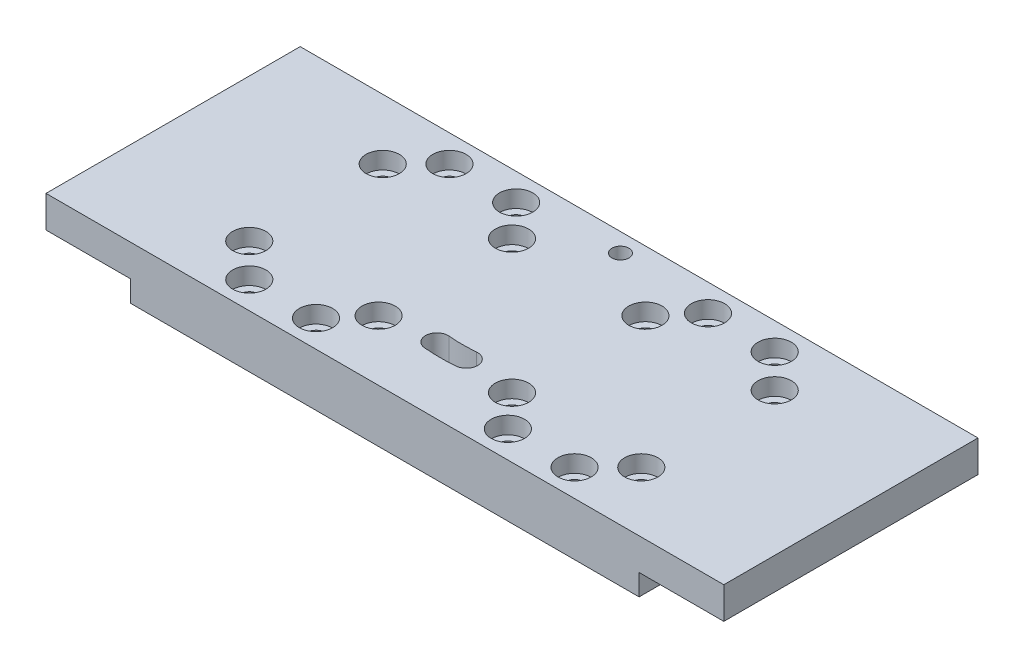
SolidWorks part; units mm, degrees
ref_plane "Front Plane" through (0, 0, 0) normal (0, 0, 1) x (1, 0, 0)
ref_plane "Top Plane" through (0, 0, 0) normal (0, 1, 0) x (1, 0, 0)
ref_plane "Right Plane" through (0, 0, 0) normal (1, 0, 0) x (0, 0, -1)
sketch "Sketch1" plane through (0, 0, 0) normal (0, 1, 0) x (1, 0, 0)
  line L1 (-101.6, -38.1) -> (101.6, -38.1)
  line L2 (-101.6, -38.1) -> (-101.6, 38.1)
  line L3 (-101.6, 38.1) -> (101.6, 38.1)
  line L4 (101.6, -38.1) -> (101.6, 38.1)
  line L5 (-101.6, -38.1) -> (101.6, 38.1) construction
  line L6 (-101.6, 38.1) -> (101.6, -38.1) construction
  point P0 (0, 0)
  dimension "D1" = 76.2
  dimension "D2" = 203.2
extrude "Boss-Extrude1" add sketch "Sketch1" along normal blind 15.875
hole_wizard "1/4-20 Tapped Hole1" positions "Sketch2" profile "Sketch3" tap size "1/4-20" standard "ANSI Inch" end condition through all
sketch "Sketch2" plane through (0, 15.875, 0) normal (0, 1, 0) x (1, 0, 0)
  point P0 (0, 32.5)
cosmetic thread "Hole Thread1" parameters "D2"=6.35
sketch "Sketch3" plane through (0, 15.875, -32.5) normal (1, 0, 0) x (0, 0, 1)
  line L0 (0, 0) -> (0, 15.875)
  line L1 (0, 15.875) -> (2.5527, 15.875)
  line L2 (2.5527, 15.875) -> (2.5527, 0)
  line L5 (2.5527, 0) -> (0, 0)
  line L11 (0, -6.35) -> (0, 107.95) construction
  dimension "Thru Tap Drill Dia." = 5.1054
  dimension "Thru Tap Drill Depth" = 15.875
sketch "Sketch4" plane through (0, 15.875, 0) normal (0, 1, 0) x (1, 0, 0)
  line L0 (0, -18.3) -> (0, 32.5) construction
  arc A0 (-4.4275, -18.1067) -> (4.4275, -18.1067) centre (0, 32.5) ccw construction
  arc A1 (-4.7215, -21.4673) -> (4.7215, -21.4673) centre (0, 32.5) ccw
  arc A2 (-4.1335, -14.7461) -> (4.1335, -14.7461) centre (0, 32.5) ccw
  arc A3 (-4.1335, -14.7461) -> (-4.7215, -21.4673) centre (-4.4275, -18.1067) ccw
  arc A4 (4.7215, -21.4673) -> (4.1335, -14.7461) centre (4.4275, -18.1067) ccw
  point P4 (0, -18.3)
  dimension "D3" = 3.3734
  dimension "D1" = 10
  dimension "D2" = 50.8
extrude "Cut-Extrude1" cut sketch "Sketch4" against normal through all contours A4 A2 A3 A1
sketch "Sketch6" plane through (0, 0, 0) normal (0, -1, 0) x (1, 0, 0)
  arc A0 (9.9106, 17.3239) -> (-9.9106, 17.3239) centre (0, -32.5) ccw construction
  arc A1 (11.1494, 23.5519) -> (-11.1494, 23.5519) centre (0, -32.5) ccw
  arc A2 (8.6718, 11.0959) -> (-8.6718, 11.0959) centre (0, -32.5) ccw
  arc A3 (8.6718, 11.0959) -> (11.1494, 23.5519) centre (9.9106, 17.3239) ccw
  arc A4 (-11.1494, 23.5519) -> (-8.6718, 11.0959) centre (-9.9106, 17.3239) ccw
  point P3 (0, 18.3)
  dimension "D2" = 22.5
  dimension "D3" = 6.35
extrude "Cut-Extrude2" cut sketch "Sketch6" against normal blind 6.35
sketch "Sketch9" plane through (0, 15.875, 0) normal (0, 1, 0) x (1, 0, 0)
  line L0 (-101.6, 0) -> (0, 0) construction
  line L1 (0, 0) -> (0, 38.1) construction
  line L2 (-101.6, 38.1) -> (-101.6, -38.1) construction
  line L3 (101.6, 38.1) -> (-101.6, 38.1) construction
  circle A0 centre (-48.755, 30) radius 2.1 construction
  circle A3 centre (-28.755, 30) radius 2.1 construction
  circle A4 centre (-20, 20) radius 2.1 construction
  circle A5 centre (-58.76, 20) radius 2.1 construction
  point P0 (-58.76, 20)
  point P1 (-48.755, 30)
  point P2 (-28.755, 30)
  point P3 (-20, 20)
  point P7 (-28.755, -30)
  point P8 (-20, -20)
  point P9 (-58.76, -20)
  point P10 (-48.755, -30)
  point P11 (28.755, 30)
  point P12 (20, 20)
  point P13 (20, -20)
  point P14 (28.755, -30)
  point P15 (48.755, -30)
  point P16 (58.76, -20)
  point P17 (48.755, 30)
  point P18 (58.76, 20)
hole_wizard "CBORE for M5 SHCS2" positions "Sketch10" profile "Sketch11" counterbore size "M5" standard "ANSI Metric" end condition through all
sketch "Sketch10" plane through (0, 15.875, 0) normal (0, 1, 0) x (1, 0, 0)
  point P0 (58.76, -20)
  point P3 (48.755, -30)
  point P6 (28.755, -30)
  point P9 (20, -20)
  point P12 (20, 20)
  point P15 (28.755, 30)
  point P18 (48.755, 30)
  point P21 (58.76, 20)
  point P24 (-28.755, 30)
  point P27 (-20, 20)
  point P30 (-48.755, 30)
  point P33 (-58.76, 20)
  point P36 (-58.76, -20)
  point P39 (-48.755, -30)
  point P42 (-28.755, -30)
  point P45 (-20, -20)
sketch "Sketch11" plane through (58.76, 15.875, 20) normal (1, 0, 0) x (0, 0, 1)
  line L0 (0, 0) -> (0, 15.875)
  line L1 (0, 15.875) -> (2.75, 15.875)
  line L3 (2.75, 15.875) -> (2.75, 5.1)
  line L4 (2.75, 5.1) -> (5, 5.1)
  line L5 (5, 5.1) -> (5, 0)
  line L7 (5, 0) -> (0, 0)
  line L11 (0, -6.35) -> (0, 107.95) construction
  dimension "Thru Hole Dia." = 5.5
  dimension "Thru Hole Depth" = 15.875
  dimension "C'Bore Dia." = 10
  dimension "C'Bore Depth" = 5.1
sketch "Sketch12" plane through (0, 0, 0) normal (0, -1, 0) x (1, 0, 0)
  line L0 (-101.6, 38.1) -> (101.6, 38.1) construction
  line L1 (101.6, -38.1) -> (76.2, -38.1)
  line L2 (101.6, -38.1) -> (101.6, 38.1)
  line L3 (101.6, 38.1) -> (76.2, 38.1)
  line L4 (76.2, -38.1) -> (76.2, 38.1)
  dimension "D1" = 25.4
extrude "Cut-Extrude3" cut sketch "Sketch12" against normal blind 6.35
mirror "Mirror1" about plane through (0, 0, 0) normal (1, 0, 0) of "Cut-Extrude3"
